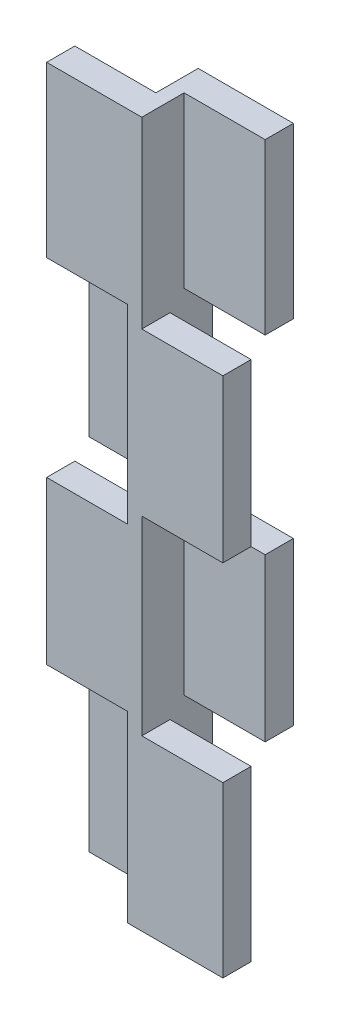
SolidWorks part; units mm, degrees
ref_plane "Front Plane" through (0, 0, 0) normal (0, 0, 1) x (1, 0, 0)
ref_plane "Top Plane" through (0, 0, 0) normal (0, 1, 0) x (1, 0, 0)
ref_plane "Right Plane" through (0, 0, 0) normal (1, 0, 0) x (0, 0, -1)
sketch "Sketch1" plane through (0, 0, 0) normal (0, 0, 1) x (1, 0, 0)
  line L1 (0, 0) -> (0.25, 0)
  line L2 (0, 0) -> (0, 1)
  line L3 (0, 1) -> (0.25, 1)
  line L4 (0.25, 0) -> (0.25, 1)
  dimension "D1" = 0.25
  dimension "D2" = 1
extrude "Boss-Extrude1" add sketch "Sketch1" along normal blind 0.1 contours L2 L3 L4 L1
sketch "Sketch2" plane through (0, 0, 0) normal (-1, 0, 0) x (0, 0, 1)
  line L0 (0.05, 1) -> (0.05, 0) construction
  line L1 (0.1, 1) -> (0, 1) construction
  line L2 (0.1, 0) -> (0, 0) construction
  line L3 (0.04, 1) -> (0.04, 0) construction
  line L4 (0.06, 1) -> (0.06, 0) construction
  line L5 (0, 0.5) -> (0.1, 0.5) construction
  line L6 (0, 0) -> (0, 1) construction
  line L7 (0.1, 0) -> (0.1, 1) construction
  line L8 (0, 0.51) -> (0.1, 0.51) construction
  line L9 (0, 0.49) -> (0.1, 0.49) construction
  line L10 (0, 0.75) -> (0.1, 0.75) construction
  line L11 (0, 0.76) -> (0.1, 0.76) construction
  line L12 (0, 0.74) -> (0.1, 0.74) construction
  line L13 (0, 0.25) -> (0.1, 0.25) construction
  line L14 (0, 0.26) -> (0.1, 0.26) construction
  line L15 (0, 0.24) -> (0.1, 0.24) construction
  line L16 (0.04, 0) -> (0.1, 0)
  line L17 (0.1, 0) -> (0.1, 0.26)
  line L18 (0.1, 0.26) -> (0.06, 0.26)
  line L19 (0.06, 0.26) -> (0.06, 0.49)
  line L20 (0.06, 0.49) -> (0.1, 0.49)
  line L21 (0.1, 0.49) -> (0.1, 0.76)
  line L22 (0.1, 0.76) -> (0.06, 0.76)
  line L23 (0.06, 0.76) -> (0.06, 1)
  line L24 (0.06, 1) -> (0, 1)
  line L25 (0, 1) -> (0, 0.74)
  line L26 (0, 0.74) -> (0.04, 0.74)
  line L27 (0.04, 0.74) -> (0.04, 0.51)
  line L28 (0.04, 0.51) -> (0, 0.51)
  line L29 (0, 0.51) -> (0, 0.24)
  line L30 (0, 0.24) -> (0.04, 0.24)
  line L31 (0.04, 0.24) -> (0.04, 0)
  dimension "D1" = 0.25
  dimension "D2" = 0.25
  dimension "D3" = 0.01
  dimension "D4" = 0.01
  dimension "D5" = 0.01
  dimension "D6" = 0.01
  dimension "D7" = 0.01
  dimension "D8" = 0.01
  dimension "D9" = 0.01
  dimension "D10" = 0.01
extrude "Cut-Extrude1" cut sketch "Sketch2" against normal blind 0.115
sketch "Sketch3" plane through (0.25, 0, 0) normal (1, 0, 0) x (0, 0, -1)
  line L0 (-0.05, 1) -> (-0.05, 0) construction
  line L1 (-0.1, 1) -> (0, 1) construction
  line L2 (-0.1, 0) -> (0, 0) construction
  line L3 (-0.06, 1) -> (-0.06, 0) construction
  line L4 (-0.04, 0) -> (-0.04, 1) construction
  line L5 (-0.1, 0.5) -> (0, 0.5) construction
  line L6 (-0.1, 0) -> (-0.1, 1) construction
  line L7 (0, 0) -> (0, 1) construction
  line L8 (-0.1, 0.51) -> (0, 0.51) construction
  line L9 (0, 0.49) -> (-0.1, 0.49) construction
  line L10 (-0.1, 0.7498) -> (0, 0.7498) construction
  line L11 (-0.1, 0.7398) -> (0, 0.7398) construction
  line L12 (-0.1, 0.7598) -> (0, 0.7598) construction
  line L13 (0, 0.25) -> (-0.1, 0.25) construction
  line L14 (-0.1, 0.26) -> (0, 0.26) construction
  line L15 (-0.04, 1) -> (-0.1, 1)
  line L16 (-0.1, 0.24) -> (0, 0.24) construction
  line L17 (-0.1, 1) -> (-0.1, 0.7398)
  line L18 (-0.1, 0.7398) -> (-0.06, 0.7398)
  line L19 (-0.06, 0.7398) -> (-0.06, 0.51)
  line L20 (-0.06, 0.51) -> (-0.1, 0.51)
  line L21 (-0.1, 0.51) -> (-0.1, 0.24)
  line L22 (-0.1, 0.24) -> (-0.06, 0.24)
  line L23 (-0.06, 0.24) -> (-0.06, 0)
  line L24 (-0.06, 0) -> (0, 0)
  line L25 (0, 0) -> (0, 0.26)
  line L26 (0, 0.26) -> (-0.04, 0.26)
  line L27 (-0.04, 0.26) -> (-0.04, 0.49)
  line L28 (-0.04, 0.49) -> (0, 0.49)
  line L29 (0, 0.49) -> (0, 0.7598)
  line L30 (0, 0.7598) -> (-0.04, 0.7598)
  line L31 (-0.04, 0.7598) -> (-0.04, 1)
  dimension "D3" = 0.01
  dimension "D4" = 0.01
  dimension "D6" = 0.01
  dimension "D7" = 0.01
  dimension "D9" = 0.01
  dimension "D10" = 0.01
  dimension "D1" = 0.01
  dimension "D2" = 0.01
  dimension "D5" = 0.2498
  dimension "D8" = 0.25
extrude "Cut-Extrude2" cut sketch "Sketch3" against normal blind 0.115
equation "\"t\"= 0.25'thickness of the sheets"
equation "\"t_cf\" = 0.115'thickness of single carbon fiber layer"
equation "\"t_kapton\" = 0.025'thickness of single Kapton flex layer"
equation "\"t_fr4\" = 0.1'thickness of FR4 with copper layer"
equation "\"joint_flex\"= 0.1'Width of flextures gap"
equation "\"joint_flex_eff\"= 0.02'Width of flecture after castelation"
equation "\"joint_fold\"= 0.2'Width of folding joints for 90deg fold"
equation "\"gap_tolerance\"= 0.002'Width to have interfecence fit between carbon fiber inserts"
equation "\"assemble_angle\"= 90'Angle of assembly parts"
equation "\"link_lift\"= 0.5'Actuation linkage amplification for the lift motion"
equation "\"link_swing\"= 0.45'Actuation linkage amplification for the swing motion"
equation "\"D1@Sketch1\"=\"t\""
equation "\"D1@Boss-Extrude1\"=\"joint_flex\""
equation "\"fold_gap\"= 0.01"
equation "\"D3@Sketch2\"=\"joint_flex_eff\"/2"
equation "\"D4@Sketch2\"=\"joint_flex_eff\"/2"
equation "\"D5@Sketch2\"=\"fold_gap\""
equation "\"D6@Sketch2\"=\"fold_gap\""
equation "\"D7@Sketch2\"=\"fold_gap\""
equation "\"D8@Sketch2\"=\"fold_gap\""
equation "\"D9@Sketch2\"=\"fold_gap\""
equation "\"D10@Sketch2\"=\"fold_gap\""
equation "\"D1@Cut-Extrude1\"=\"t_cf\""
equation "\"D1@Sketch3\"=\"joint_flex_eff\"/2"
equation "\"D2@Sketch3\"=\"joint_flex_eff\"/2"
equation "\"D3@Sketch3\"=\"fold_gap\""
equation "\"D4@Sketch3\"=\"fold_gap\""
equation "\"D6@Sketch3\"=\"fold_gap\""
equation "\"D7@Sketch3\"=\"fold_gap\""
equation "\"D9@Sketch3\"=\"fold_gap\""
equation "\"D10@Sketch3\"=\"fold_gap\""
equation "\"D1@Cut-Extrude2\"=\"t_cf\""
